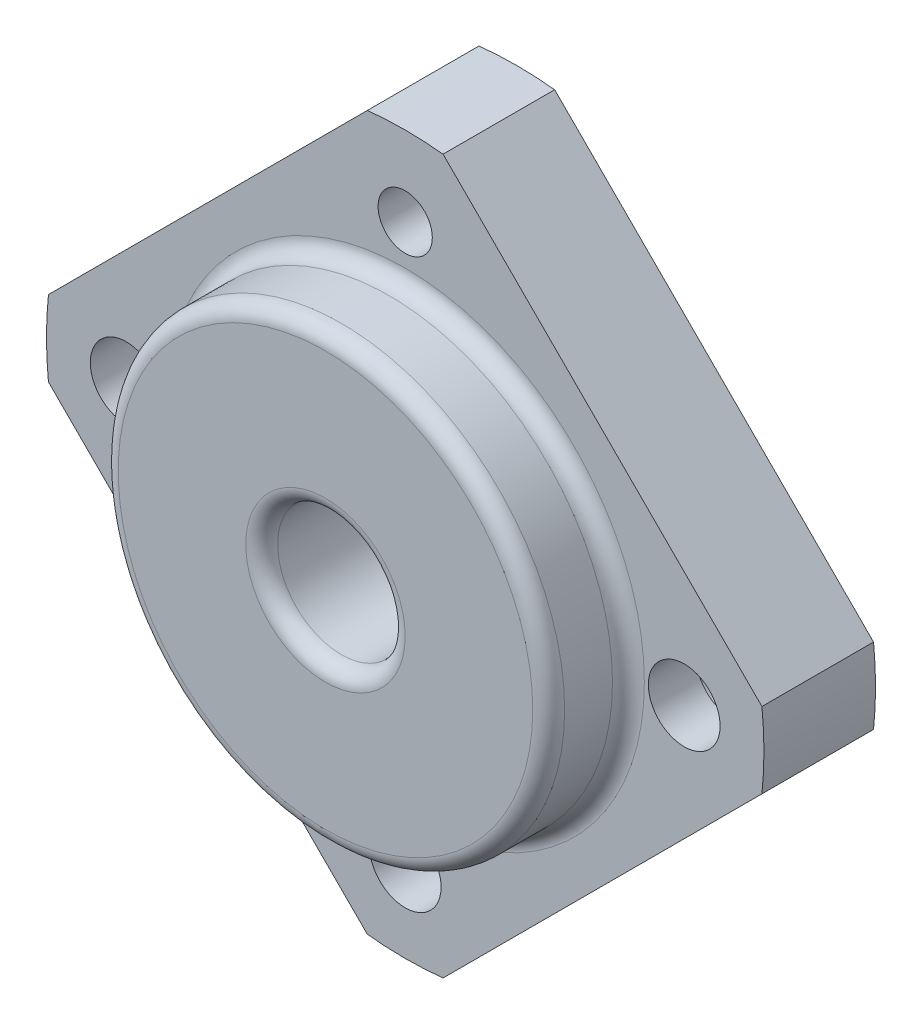
SolidWorks part; units mm, degrees
ref_plane "Front Plane" through (0, 0, 0) normal (0, 0, 1) x (1, 0, 0)
ref_plane "Top Plane" through (0, 0, 0) normal (0, 1, 0) x (1, 0, 0)
ref_plane "Right Plane" through (0, 0, 0) normal (1, 0, 0) x (0, 0, -1)
sketch "Sketch1" plane through (0, 0, 0) normal (0, 0, 1) x (1, 0, 0)
  line L0 (0, 0) -> (-12.3744, 12.3744) construction
  line L1 (-12.3744, -12.3744) -> (-22.3744, -2.3744)
  line L2 (-12.3744, -12.3744) -> (-2.3744, -22.3744)
  line L3 (0, 0) -> (12.3744, -12.3744) construction
  line L4 (12.3744, 12.3744) -> (2.3744, 22.3744)
  line L5 (12.3744, 12.3744) -> (22.3744, 2.3744)
  line L6 (-12.3744, 12.3744) -> (-22.3744, 2.3744)
  line L7 (-12.3744, 12.3744) -> (-2.3744, 22.3744)
  line L8 (12.3744, -12.3744) -> (22.3744, -2.3744)
  line L9 (12.3744, -12.3744) -> (2.3744, -22.3744)
  line L10 (0, 0) -> (12.3744, 12.3744) construction
  line L11 (0, 0) -> (-12.3744, -12.3744) construction
  arc A0 (-2.3744, -22.3744) -> (2.3744, -22.3744) centre (0, 0) ccw
  arc A8 (22.3744, -2.3744) -> (22.3744, 2.3744) centre (0, 0) ccw
  arc A9 (2.3744, 22.3744) -> (-2.3744, 22.3744) centre (0, 0) ccw
  arc A10 (-22.3744, 2.3744) -> (-22.3744, -2.3744) centre (0, 0) ccw
  dimension "D1" = 45
  dimension "D2" = 35
extrude "Boss-Extrude1" add sketch "Sketch1" along normal blind 7
sketch "Sketch2" plane through (0, 0, 0) normal (0, 0, -1) x (-1, 0, 0)
  circle A0 centre (0, 0) radius 17.5
  circle A1 centre (0, 17.5) radius 3.25
  circle A2 centre (-17.5, 0) radius 3.25
  circle A3 centre (0, -17.5) radius 3.25
  circle A4 centre (17.5, 0) radius 3.25
  dimension "D1" = 35
  dimension "D2" = 6.5
extrude "Cut-Extrude1" cut sketch "Sketch2" against normal blind 4 contours A2 | A1 | A4 | A3
sketch "Sketch3" plane through (0, 0, 4) normal (0, 0, -1) x (-1, 0, 0)
  circle A0 centre (0, 17.5) radius 1.7
  circle A1 centre (-17.5, 0) radius 2.25
  circle A2 centre (17.5, 0) radius 2.25
  circle A3 centre (0, -17.5) radius 2.25
  dimension "D1" = 3.4
extrude "Cut-Extrude2" cut sketch "Sketch3" against normal blind 4
sketch "Sketch4" plane through (0, 0, 7) normal (0, 0, 1) x (1, 0, 0)
  circle A0 centre (0, 0) radius 14
  dimension "D1" = 28
extrude "Boss-Extrude2" add sketch "Sketch4" along normal blind 5
sketch "Sketch5" plane through (0, 0, 12) normal (0, 0, 1) x (1, 0, 0)
  circle A0 centre (0, 0) radius 4
  dimension "D1" = 8
extrude "Cut-Extrude3" cut sketch "Sketch5" against normal blind 15
fillet "Fillet3" radius 1 3 edges at (14, 0, 7) (14, 0, 12) (4, 0, 12)
